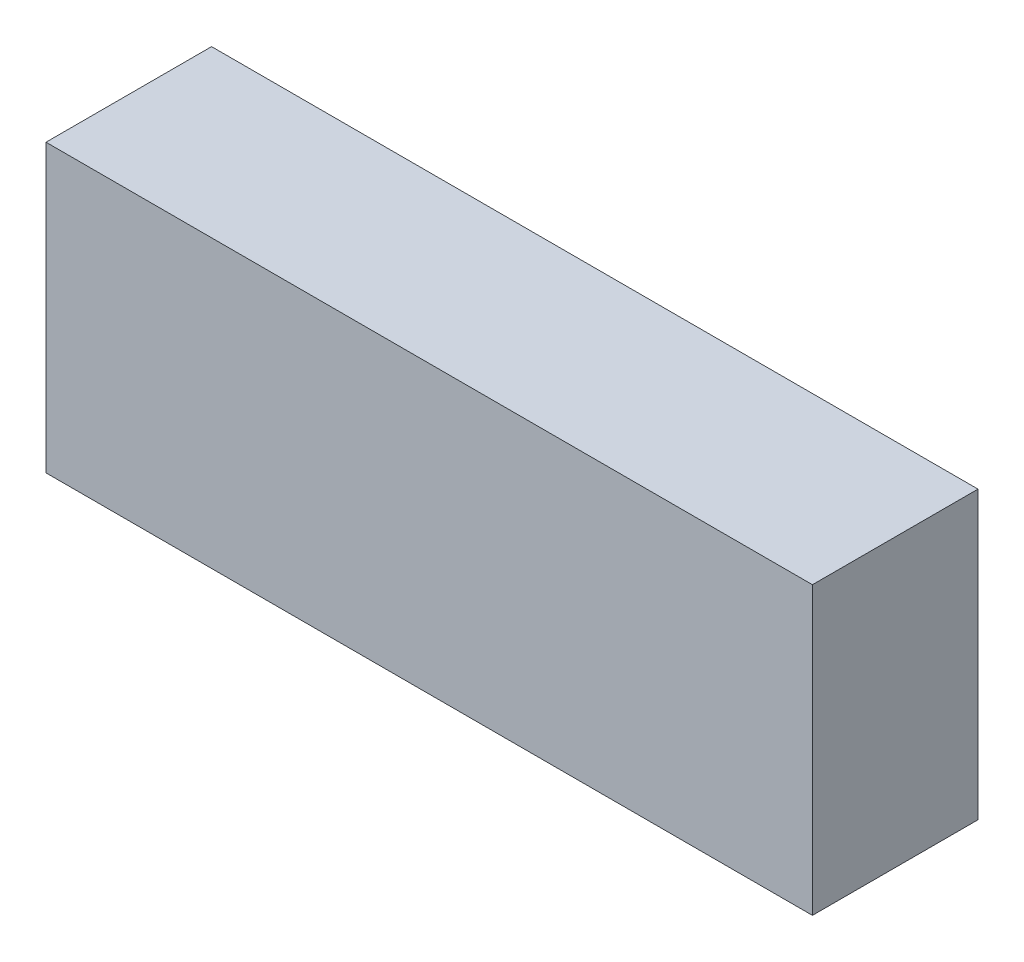
SolidWorks part; units mm, degrees
ref_plane "Front Plane" through (0, 0, 0) normal (0, 0, 1) x (1, 0, 0)
ref_plane "Top Plane" through (0, 0, 0) normal (0, 1, 0) x (1, 0, 0)
ref_plane "Right Plane" through (0, 0, 0) normal (1, 0, 0) x (0, 0, -1)
sketch "Sketch1" plane through (0, 0, 0) normal (0, 0, 1) x (1, 0, 0)
  line L0 (-16.9755, 14.45) -> (16.9845, 14.45) construction
  line L1 (-16.7755, 14.25) -> (16.7845, 14.25)
  line L2 (-16.7755, 14.25) -> (-16.7755, 1.71)
  line L3 (-16.7755, 1.71) -> (16.7845, 1.71)
  line L4 (16.7845, 14.25) -> (16.7845, 1.71)
  line L5 (16.9845, 14.45) -> (16.9845, 1.51) construction
  line L6 (16.9845, 1.51) -> (-16.9755, 1.51) construction
  line L7 (-16.9755, 1.51) -> (-16.9755, 14.45) construction
  dimension "D1" = 0.2
  dimension "D2" = 0.2
  dimension "D3" = 0.2
  dimension "D4" = 0.2
extrude "Boss-Extrude1" add sketch "Sketch1" along normal blind 7.25
shell "Shell1" thickness 0.5
equation "\"D2@Sketch1\"=\"D1@Sketch1\""
equation "\"D3@Sketch1\"=\"D1@Sketch1\""
equation "\"D4@Sketch1\"=\"D1@Sketch1\""
